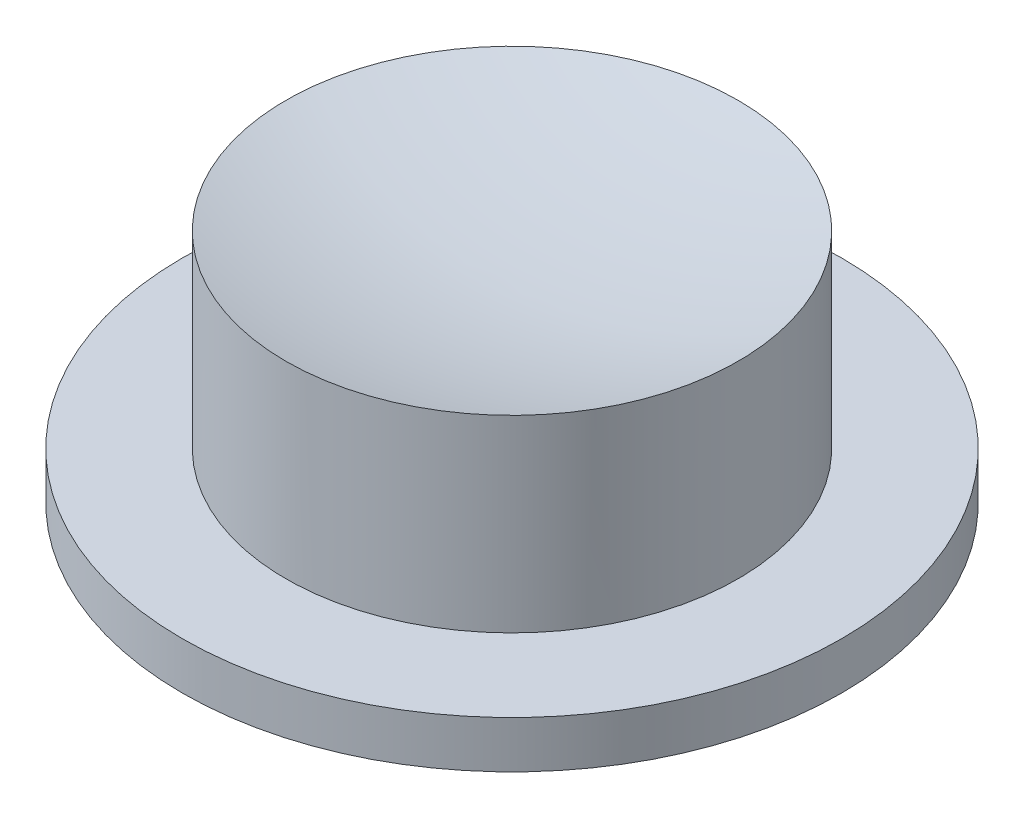
SolidWorks part; units mm, degrees
ref_plane "Front Plane" through (0, 0, 0) normal (0, 0, 1) x (1, 0, 0)
ref_plane "Top Plane" through (0, 0, 0) normal (0, 1, 0) x (1, 0, 0)
ref_plane "Right Plane" through (0, 0, 0) normal (1, 0, 0) x (0, 0, -1)
sketch "Эскиз1" plane through (0, 0, 0) normal (0, 1, 0) x (1, 0, 0)
  circle A0 centre (0, 0) radius 2.4
  dimension "D1" = 4.8
extrude "Бобышка-Вытянуть1" add sketch "Эскиз1" along normal blind 2.5
sketch "Эскиз2" plane through (0, 0, 0) normal (1, 0, 0) x (0, 0, -1)
  line L0 (0, 2.5) -> (0, 10.5306) construction
  line L1 (2.4, 2.5) -> (-2.4, 2.5) construction
  line L2 (0, 2.5) -> (0, 2.149)
  line L3 (0, 2.149) -> (0, 2.5)
  line L4 (0, 2.5) -> (2.4, 2.5)
  arc A0 (0, 2.149) -> (2.4, 2.5) centre (0, 10.5306) ccw
  dimension "D1" = 8.3815
revolve "Вырез-Повернуть1" cut sketch "Эскиз2" angle 360 about L0
sketch "Эскиз3" plane through (0, 0, 0) normal (0, -1, 0) x (1, 0, 0)
  circle A0 centre (0, 0) radius 3.5
extrude "Бобышка-Вытянуть2" add sketch "Эскиз3" against normal blind 0.5
